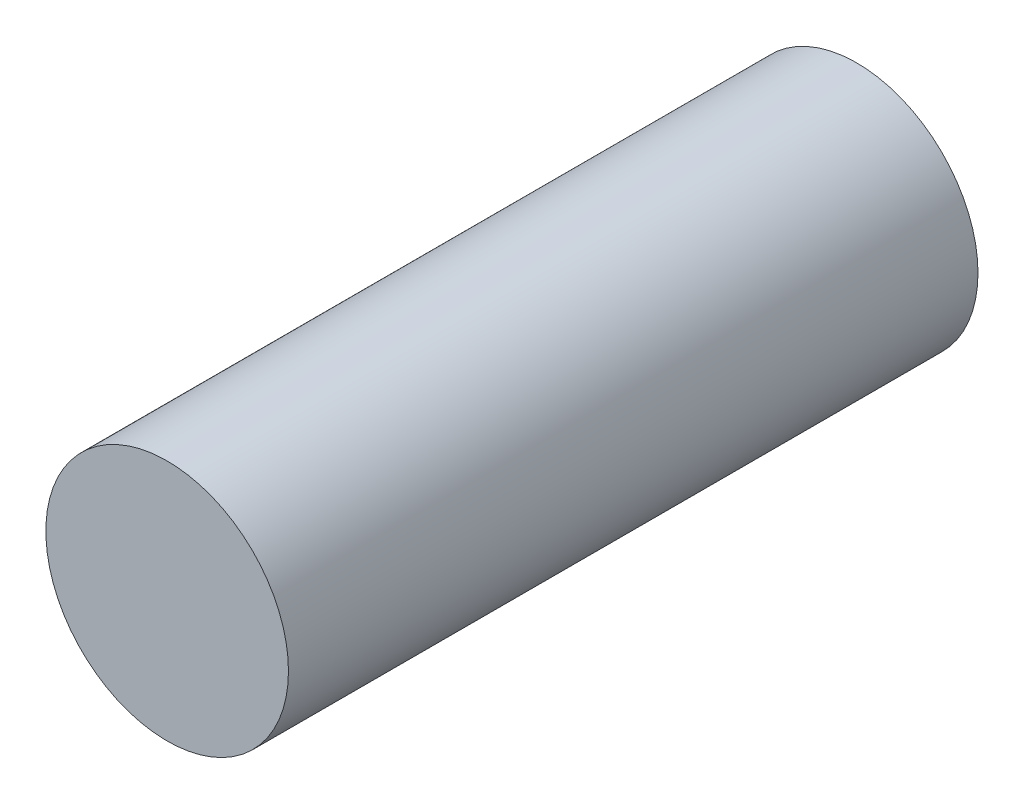
SolidWorks part; units mm, degrees
ref_plane "Спереди" through (0, 0, 0) normal (0, 0, 1) x (1, 0, 0)
ref_plane "Сверху" through (0, 0, 0) normal (0, 1, 0) x (1, 0, 0)
ref_plane "Справа" through (0, 0, 0) normal (1, 0, 0) x (0, 0, -1)
other "Configuration Table"
sketch "Эскиз1" plane through (0, 0, 0) normal (0, 0, 1) x (1, 0, 0)
  circle A0 centre (0, 0) radius 9.5
  dimension "D1" = 19
extrude "Бобышка-Вытянуть1" add sketch "Эскиз1" along normal blind 54 contours A0
